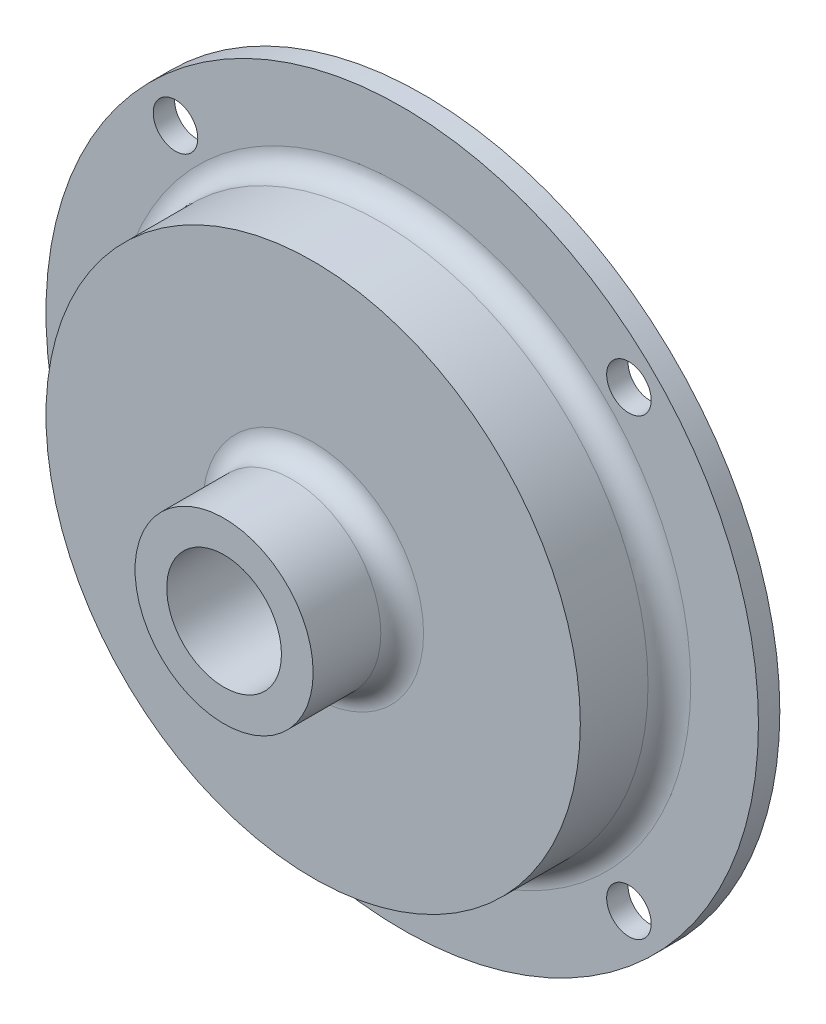
SolidWorks part; units mm, degrees
material "PW40:6:Sc:0:Re:24:"
ref_plane "Front" through (0, 0, 0) normal (0, 0, 1) x (1, 0, 0)
ref_plane "Top" through (0, 0, 0) normal (0, 1, 0) x (1, 0, 0)
ref_plane "Right" through (0, 0, 0) normal (1, 0, 0) x (0, 0, -1)
sketch "Sketch1" plane through (0, 0, 0) normal (0, 0, 1) x (1, 0, 0)
  line L0 (0, 0) -> (50, 0) construction
  line L1 (0, 0) -> (35.3553, 35.3553) construction
  line L2 (0, 0) -> (-35.3553, 35.3553) construction
  circle A0 centre (0, 0) radius 50
  circle A1 centre (0, 0) radius 45 construction
  circle A2 centre (31.8198, 31.8198) radius 3.125
  circle A4 centre (-31.8198, -31.8198) radius 3.125
  circle A6 centre (31.8198, -31.8198) radius 3.125
  circle A7 centre (-31.8198, 31.8198) radius 3.125
  dimension "D1" = 100
  dimension "D3" = 6.25
  dimension "D4" = 90
  dimension "D2" = 45
extrude "Base-Extrude" add sketch "Sketch1" along normal blind 3
sketch "Sketch2" plane through (0, 0, 3) normal (0, 0, 1) x (1, 0, 0)
  circle A0 centre (0, 0) radius 37.5
  dimension "D1" = 75
extrude "Boss-Extrude1" add sketch "Sketch2" along normal blind 12.5
sketch "Sketch3" plane through (0, 0, 15.5) normal (0, 0, 1) x (1, 0, 0)
  circle A0 centre (0, 0) radius 12.5
  dimension "D1" = 25
extrude "Boss-Extrude2" add sketch "Sketch3" along normal blind 12.5
fillet "Fillet1" radius 3 2 edges at (37.5, 0, 3) (12.5, 0, 15.5)
sketch "Sketch4" plane through (0, 0, 28) normal (0, 0, 1) x (1, 0, 0)
  circle A0 centre (0, 0) radius 8.05
  dimension "D1" = 16.1
extrude "Cut-Extrude1" cut sketch "Sketch4" against normal through all
